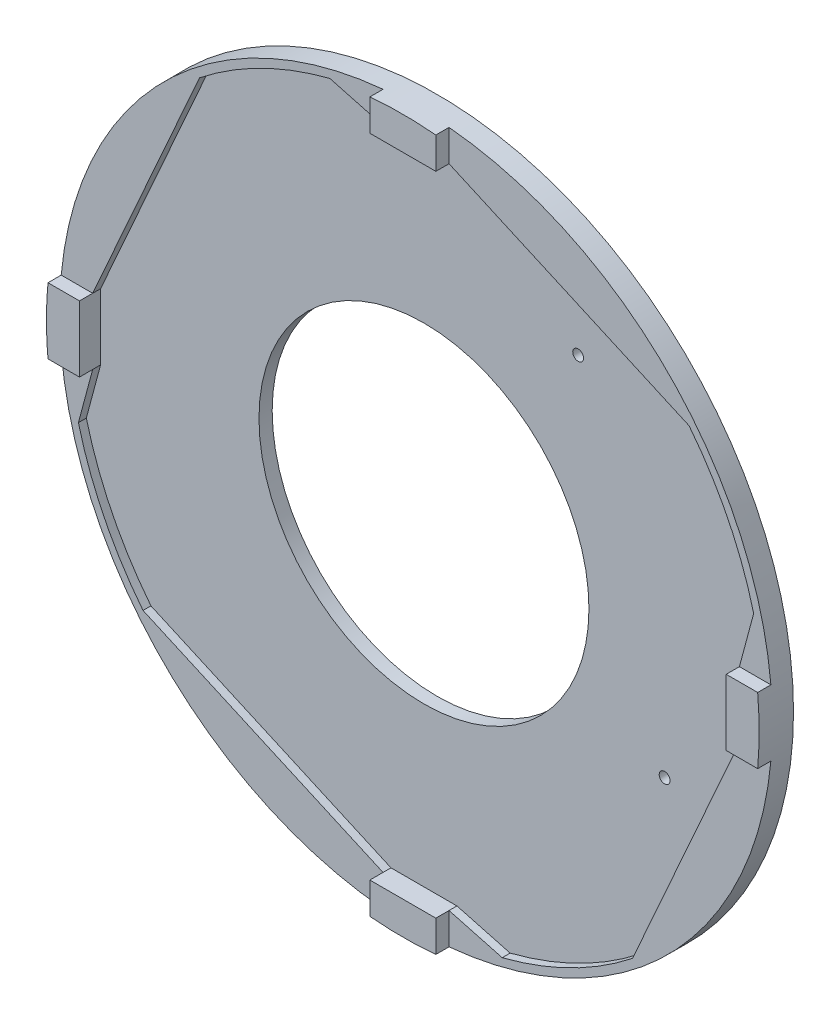
SolidWorks part; units mm, degrees
ref_plane "Piano frontale" through (0, 0, 0) normal (0, 0, 1) x (1, 0, 0)
ref_plane "Piano superiore" through (0, 0, 0) normal (0, 1, 0) x (1, 0, 0)
ref_plane "Piano destro" through (0, 0, 0) normal (1, 0, 0) x (0, 0, -1)
sketch "Schizzo1" plane through (0, 0, 0) normal (0, 0, 1) x (1, 0, 0)
  circle A0 centre (0, 0) radius 135
  dimension "D1" = 270
extrude "Estrusione-Estrusione2" add sketch "Schizzo1" along normal blind 3
sketch "Schizzo4" plane through (0, 0, 3) normal (0, 0, 1) x (1, 0, 0)
  circle A0 centre (0, 0) radius 132
  dimension "D1" = 264
extrude "Taglio-Estrusione1" cut sketch "Schizzo4" against normal through all
sketch "Schizzo5" plane through (0, 0, 0) normal (0, 0, -1) x (-1, 0, 0)
  line L0 (0, 0) -> (0, 135) construction
  line L2 (12.5, 147.5) -> (-12.5, 147.5) construction
  line L3 (12.5, 147.5) -> (12.5, 122.5) construction
  line L4 (12.5, 122.5) -> (-12.5, 122.5) construction
  line L5 (-12.5, 147.5) -> (-12.5, 122.5) construction
  line L6 (12.5, 147.5) -> (-12.5, 122.5) construction
  line L7 (12.5, 122.5) -> (-12.5, 147.5) construction
  line L9 (-12.5, 134.4201) -> (-12.5, 122.5)
  line L10 (-12.5, 122.5) -> (12.5, 122.5)
  line L11 (12.5, 134.4201) -> (12.5, 122.5)
  circle A0 centre (0, 0) radius 135 construction
  arc A2 (12.5, 134.4201) -> (-12.5, 134.4201) centre (0, 0) ccw
  dimension "D4" = 135
  dimension "D1" = 25
  dimension "D2" = 25
extrude "Estrusione-Estrusione3" add sketch "Schizzo5" against normal blind 8
pattern_circular "RipetizioneCircolare2" count 4 every 90 about axis through (0, 0, 0) along (0, 0, 1) of "Estrusione-Estrusione3"
sketch "Schizzo8" plane through (0, 0, 0) normal (0, 0, -1) x (-1, 0, 0)
  line L2 (-12.5, 122.5) -> (12.5, 122.5)
  line L3 (12.5, 122.5) -> (32.6483, 127.8987)
  line L4 (12.5, 122.5) -> (12.5, 131.4068) construction
  line L5 (-12.5, 122.5) -> (-103.4279, 82.0163)
  line L6 (-12.5, 131.4068) -> (-12.5, 122.5) construction
  circle A3 centre (0, 0) radius 132 construction
  circle A5 centre (0, 0) radius 132 construction
  arc A7 (32.6483, 127.8987) -> (-103.4279, 82.0163) centre (0, 0) ccw
  dimension "D1" = 75
  dimension "130" = 114
extrude "Estrusione-Estrusione5" add sketch "Schizzo8" against normal blind 3
pattern_circular "RipetizioneCircolare4" count 4 over 360 about axis through (0, 0, 0) along (0, 0, 1) of "Estrusione-Estrusione5"
sketch "Schizzo9" plane through (0, 0, 0) normal (0, 0, -1) x (-1, 0, 0)
  circle A0 centre (0, 0) radius 135
  dimension "D1" = 270
extrude "Estrusione-Estrusione6" add sketch "Schizzo9" along normal blind 5
sketch "Schizzo10" plane through (0, 0, -5) normal (0, 0, -1) x (-1, 0, 0)
  circle A0 centre (0, 0) radius 62.5
  dimension "D1" = 125
extrude "Taglio-Estrusione2" cut sketch "Schizzo10" against normal blind 10
sketch "Schizzo11" plane through (0, 0, -5) normal (0, 0, -1) x (-1, 0, 0)
  line L0 (0, 0) -> (-95.2628, -55) construction
  line L1 (-5, 8.6603) -> (-91.1684, -41.0891) construction
  line L2 (-5, 8.6603) -> (-100.2628, -46.3397) construction
  line L3 (0, 0) -> (-60.6377, 105.0275) construction
  line L4 (-8.6603, -5) -> (-58.4096, 81.1684) construction
  line L5 (-8.6603, -5) -> (-69.2979, 100.0275) construction
  line L6 (0, 0) -> (0, -26.6207) construction
  circle A2 centre (0, 0) radius 100 construction
  circle A3 centre (-91.1684, -41.0891) radius 2.05
  circle A4 centre (-58.4096, 81.1684) radius 2.05
  dimension "D2" = 10
  dimension "D3" = 200
  dimension "D4" = 4.1
  dimension "D5" = 4.1
  dimension "D1" = 10
  dimension "D6" = 60
extrude "Taglio-Estrusione3" cut sketch "Schizzo11" against normal blind 10
